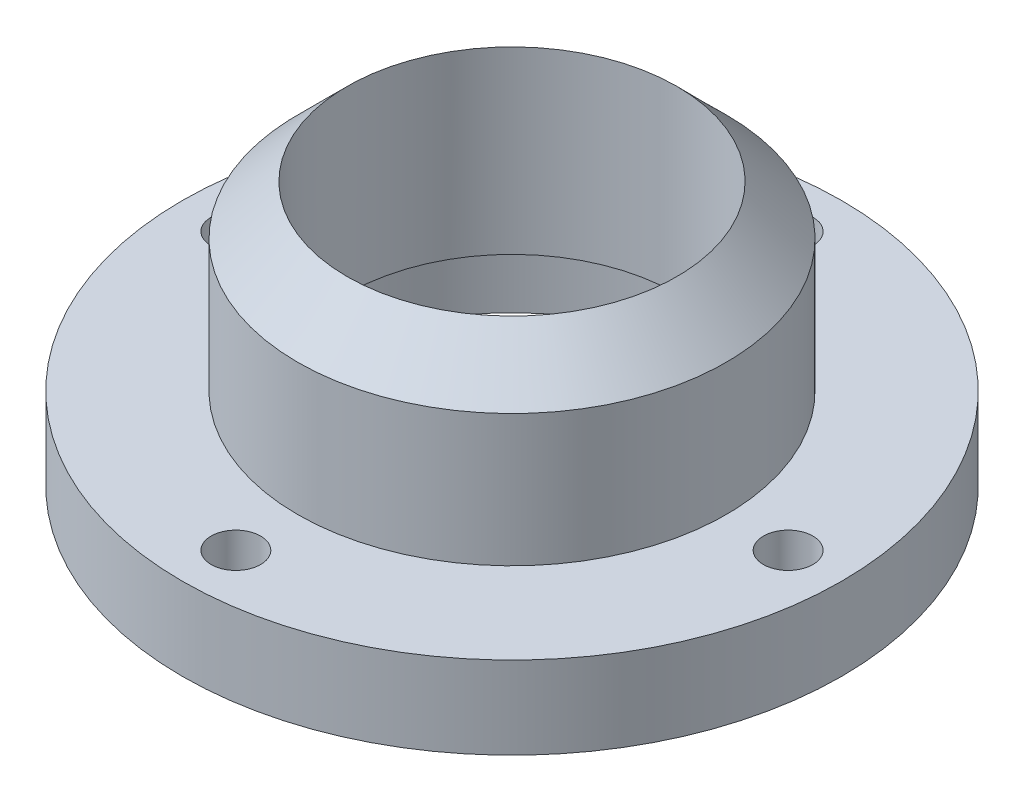
SolidWorks part; units mm, degrees
ref_plane "Front Plane" through (0, 0, 0) normal (0, 0, 1) x (1, 0, 0)
ref_plane "Top Plane" through (0, 0, 0) normal (0, 1, 0) x (1, 0, 0)
ref_plane "Right Plane" through (0, 0, 0) normal (1, 0, 0) x (0, 0, -1)
ref_plane "Plane1" through (0, 11.5, 0) normal (0, -1, 0) x (1, 0, 0)
sketch "Sketch1" plane through (0, 11.5, 0) normal (0, -1, 0) x (1, 0, 0)
  circle A0 centre (-150.0571, 0) radius 40
extrude "Boss-Extrude1" add sketch "Sketch1" against normal blind 10
sketch "Sketch2" plane through (0, 11.5, 0) normal (0, -1, 0) x (1, 0, 0)
  circle A0 centre (-150.0571, -33.5) radius 3
extrude "Cut-Extrude1" cut sketch "Sketch2" against normal through all
sketch "Sketch3" plane through (0, 11.5, 0) normal (0, -1, 0) x (1, 0, 0)
  circle A0 centre (-116.5571, 0) radius 3
extrude "Cut-Extrude2" cut sketch "Sketch3" against normal through all
sketch "Sketch4" plane through (0, 11.5, 0) normal (0, -1, 0) x (1, 0, 0)
  circle A0 centre (-150.0571, 33.5) radius 3
extrude "Cut-Extrude3" cut sketch "Sketch4" against normal through all
sketch "Sketch5" plane through (0, 21.5, 0) normal (0, 1, 0) x (-1, 0, 0)
  circle A0 centre (183.5571, 0) radius 3
extrude "Cut-Extrude4" cut sketch "Sketch5" against normal through all
sketch "Sketch6" plane through (0, 21.5, 0) normal (0, 1, 0) x (-1, 0, 0)
  circle A0 centre (150.0571, 0) radius 26
extrude "Boss-Extrude2" add sketch "Sketch6" along normal blind 16
sketch "Sketch7" plane through (0, 37.5, 0) normal (0, 1, 0) x (-1, 0, 0)
  circle A0 centre (150.0571, 0) radius 26
extrude "Boss-Extrude3" add sketch "Sketch7" along normal blind 6 draft 45
sketch "Sketch8" plane through (0, 43.5, 0) normal (0, 1, 0) x (-1, 0, 0)
  circle A0 centre (150.0571, 0) radius 20
extrude "Boss-Extrude4" add sketch "Sketch8" along normal blind 14
sketch "Sketch9" plane through (0, 11.5, 0) normal (0, -1, 0) x (1, 0, 0)
  circle A0 centre (-150.0571, 0) radius 25.75
extrude "Cut-Extrude5" cut sketch "Sketch9" against normal blind 10.2
sketch "Sketch10" plane through (0, 21.7, 0) normal (0, -1, 0) x (1, 0, 0)
  circle A0 centre (-150.0571, 0) radius 20
  dimension "D1" = 40
extrude "Cut-Extrude6" cut sketch "Sketch10" against normal through all
